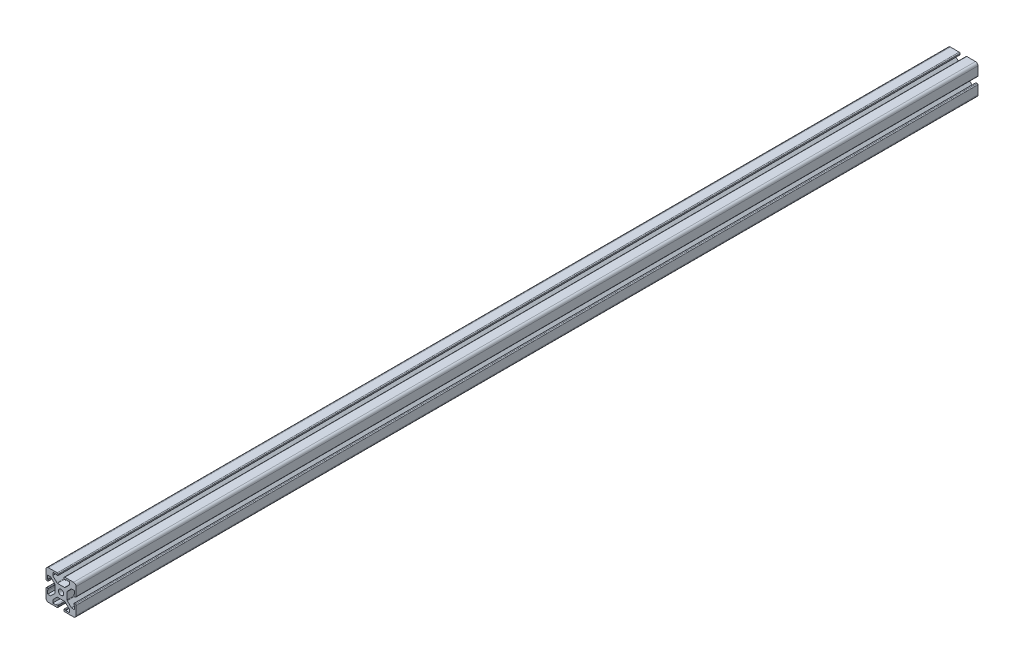
SolidWorks part; units mm, degrees
ref_plane "Front Plane" through (0, 0, 0) normal (0, 0, 1) x (1, 0, 0)
ref_plane "Top Plane" through (0, 0, 0) normal (0, 1, 0) x (1, 0, 0)
ref_plane "Right Plane" through (0, 0, 0) normal (1, 0, 0) x (0, 0, -1)
sketch "Sketch1" plane through (0, 0, 0) normal (0, 0, 1) x (1, 0, 0)
  line L120 (-8, 4.6003) -> (-8, -4.6003)
  line L121 (-8.372, -5.4983) -> (-13.8737, -11)
  line L122 (-13.8737, -11) -> (-17.7902, -11)
  line L123 (-17.7902, -11) -> (-17.7902, -6.2098)
  line L124 (-17.7902, -6.2098) -> (-17.0282, -6.2098)
  line L125 (-17.0282, -6.2098) -> (-17.0282, -4.508)
  line L126 (-17.5362, -4) -> (-18.8951, -4)
  line L127 (-20, -5.1049) -> (-20, -16.68)
  line L128 (-16.68, -20) -> (-5.1049, -20)
  line L129 (-4, -18.8951) -> (-4, -17.5362)
  line L130 (-4.508, -17.0282) -> (-6.2098, -17.0282)
  line L131 (-6.2098, -17.0282) -> (-6.2098, -17.7902)
  line L132 (-6.2098, -17.7902) -> (-11, -17.7902)
  line L133 (-11, -17.7902) -> (-11, -13.8737)
  line L134 (-11, -13.8737) -> (-5.4983, -8.372)
  line L135 (-4.6003, -8) -> (4.6003, -8)
  line L136 (5.4983, -8.372) -> (11, -13.8737)
  line L137 (11, -13.8737) -> (11, -17.7902)
  line L138 (11, -17.7902) -> (6.2098, -17.7902)
  line L139 (6.2098, -17.7902) -> (6.2098, -17.0282)
  line L140 (6.2098, -17.0282) -> (4.508, -17.0282)
  line L141 (4, -17.5362) -> (4, -18.8951)
  line L142 (5.1049, -20) -> (16.68, -20)
  line L143 (20, -16.68) -> (20, -5.1049)
  line L144 (18.8951, -4) -> (17.5362, -4)
  line L145 (17.0282, -4.508) -> (17.0282, -6.2098)
  line L146 (17.0282, -6.2098) -> (17.7902, -6.2098)
  line L147 (17.7902, -6.2098) -> (17.7902, -11)
  line L148 (17.7902, -11) -> (13.8737, -11)
  line L149 (13.8737, -11) -> (8.372, -5.4983)
  line L150 (8, -4.6003) -> (8, 4.6003)
  line L151 (8.372, 5.4983) -> (13.8737, 11)
  line L152 (13.8737, 11) -> (17.7902, 11)
  line L153 (17.7902, 11) -> (17.7902, 6.2098)
  line L154 (17.7902, 6.2098) -> (17.0282, 6.2098)
  line L155 (17.0282, 6.2098) -> (17.0282, 4.508)
  line L156 (17.5362, 4) -> (18.8951, 4)
  line L157 (20, 5.1049) -> (20, 16.68)
  line L158 (16.68, 20) -> (5.1049, 20)
  line L159 (4, 18.8951) -> (4, 17.5362)
  line L160 (4.508, 17.0282) -> (6.2098, 17.0282)
  line L161 (6.2098, 17.0282) -> (6.2098, 17.7902)
  line L162 (6.2098, 17.7902) -> (11, 17.7902)
  line L163 (11, 17.7902) -> (11, 13.8737)
  line L164 (11, 13.8737) -> (5.4983, 8.372)
  line L165 (4.6003, 8) -> (-4.6003, 8)
  line L166 (-5.4983, 8.372) -> (-11, 13.8737)
  line L167 (-11, 13.8737) -> (-11, 17.7902)
  line L168 (-11, 17.7902) -> (-6.2098, 17.7902)
  line L169 (-6.2098, 17.7902) -> (-6.2098, 17.0282)
  line L170 (-6.2098, 17.0282) -> (-4.508, 17.0282)
  line L171 (-4, 17.5362) -> (-4, 18.8951)
  line L172 (-5.1049, 20) -> (-16.68, 20)
  line L173 (-20, 16.68) -> (-20, 5.1049)
  line L174 (-18.8951, 4) -> (-17.5362, 4)
  line L175 (-17.0282, 4.508) -> (-17.0282, 6.2098)
  line L176 (-17.0282, 6.2098) -> (-17.7902, 6.2098)
  line L177 (-17.7902, 6.2098) -> (-17.7902, 11)
  line L178 (-17.7902, 11) -> (-13.8737, 11)
  line L179 (-13.8737, 11) -> (-8.372, 5.4983)
  circle A0 centre (0, 0) radius 3.5
  arc A56 (-8.372, -5.4983) -> (-8, -4.6003) centre (-9.27, -4.6003) ccw
  arc A57 (-17.0282, -4.508) -> (-17.5362, -4) centre (-17.5362, -4.508) ccw
  arc A58 (-18.8951, -4) -> (-20, -5.1049) centre (-18.8951, -5.1049) ccw
  arc A59 (-20, -16.68) -> (-16.68, -20) centre (-16.68, -16.68) ccw
  arc A60 (-5.1049, -20) -> (-4, -18.8951) centre (-5.1049, -18.8951) ccw
  arc A61 (-4, -17.5362) -> (-4.508, -17.0282) centre (-4.508, -17.5362) ccw
  arc A62 (-4.6003, -8) -> (-5.4983, -8.372) centre (-4.6003, -9.27) ccw
  arc A63 (5.4983, -8.372) -> (4.6003, -8) centre (4.6003, -9.27) ccw
  arc A64 (4.508, -17.0282) -> (4, -17.5362) centre (4.508, -17.5362) ccw
  arc A65 (4, -18.8951) -> (5.1049, -20) centre (5.1049, -18.8951) ccw
  arc A66 (16.68, -20) -> (20, -16.68) centre (16.68, -16.68) ccw
  arc A67 (20, -5.1049) -> (18.8951, -4) centre (18.8951, -5.1049) ccw
  arc A68 (17.5362, -4) -> (17.0282, -4.508) centre (17.5362, -4.508) ccw
  arc A69 (8, -4.6003) -> (8.372, -5.4983) centre (9.27, -4.6003) ccw
  arc A70 (8.372, 5.4983) -> (8, 4.6003) centre (9.27, 4.6003) ccw
  arc A71 (17.0282, 4.508) -> (17.5362, 4) centre (17.5362, 4.508) ccw
  arc A72 (18.8951, 4) -> (20, 5.1049) centre (18.8951, 5.1049) ccw
  arc A73 (20, 16.68) -> (16.68, 20) centre (16.68, 16.68) ccw
  arc A74 (5.1049, 20) -> (4, 18.8951) centre (5.1049, 18.8951) ccw
  arc A75 (4, 17.5362) -> (4.508, 17.0282) centre (4.508, 17.5362) ccw
  arc A76 (4.6003, 8) -> (5.4983, 8.372) centre (4.6003, 9.27) ccw
  arc A77 (-5.4983, 8.372) -> (-4.6003, 8) centre (-4.6003, 9.27) ccw
  arc A78 (-4.508, 17.0282) -> (-4, 17.5362) centre (-4.508, 17.5362) ccw
  arc A79 (-4, 18.8951) -> (-5.1049, 20) centre (-5.1049, 18.8951) ccw
  arc A80 (-16.68, 20) -> (-20, 16.68) centre (-16.68, 16.68) ccw
  arc A81 (-20, 5.1049) -> (-18.8951, 4) centre (-18.8951, 5.1049) ccw
  arc A82 (-17.5362, 4) -> (-17.0282, 4.508) centre (-17.5362, 4.508) ccw
  arc A83 (-8, 4.6003) -> (-8.372, 5.4983) centre (-9.27, 4.6003) ccw
  dimension "D1" = 7
extrude "Boss-Extrude1" add sketch "Sketch1" along normal mid plane 1200
